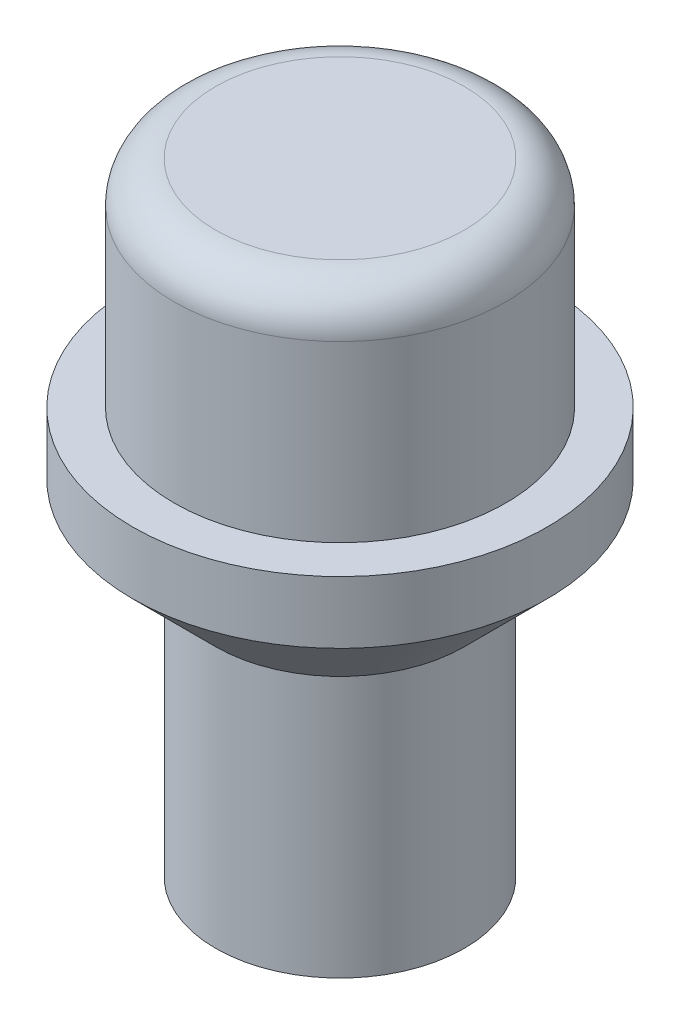
SolidWorks part; units mm, degrees
ref_plane "Спереди" through (0, 0, 0) normal (0, 0, 1) x (1, 0, 0)
ref_plane "Сверху" through (0, 0, 0) normal (0, 1, 0) x (1, 0, 0)
ref_plane "Справа" through (0, 0, 0) normal (1, 0, 0) x (0, 0, -1)
sketch "Эскиз2" plane through (0, 0, 0) normal (1, 0, 0) x (0, 0, -1)
  line L0 (0, 8.6555) -> (0, -6.1681) construction
  line L1 (0, 0) -> (3, 0)
  line L2 (3, 0) -> (3, 6.3)
  line L3 (3, 6.3) -> (5, 8.3)
  line L4 (5, 8.3) -> (5, 9.8)
  line L5 (5, 9.8) -> (4, 9.8)
  line L6 (4, 9.8) -> (4, 15)
  line L7 (4, 15) -> (0, 15)
  line L8 (0, 15) -> (0, 0)
  dimension "D1" = 8
  dimension "D2" = 10
  dimension "D3" = 5.2
  dimension "D4" = 45
  dimension "D5" = 1.5
  dimension "D6" = 6
  dimension "D7" = 9.8
revolve "Повернуть1" add sketch "Эскиз2" angle 360 about L0
fillet "Скругление1" radius 1 1 edges at (0, 15, 4)
